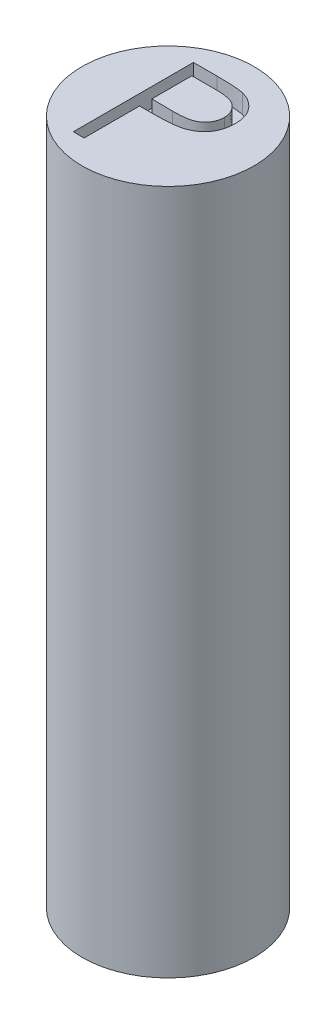
SolidWorks part; units mm, degrees
ref_plane "Front Plane" through (0, 0, 0) normal (0, 0, 1) x (1, 0, 0)
ref_plane "Top Plane" through (0, 0, 0) normal (0, 1, 0) x (1, 0, 0)
ref_plane "Right Plane" through (0, 0, 0) normal (1, 0, 0) x (0, 0, -1)
sketch "Sketch1" plane through (0, 0, 0) normal (0, 1, 0) x (1, 0, 0)
  circle A0 centre (0, 0) radius 9.1
  dimension "D1" = 18.2
extrude "Boss-Extrude1" add sketch "Sketch1" along normal blind 72.5
sketch "Sketch3" plane through (0, 72.5, 0) normal (0, 1, 0) x (1, 0, 0)
  line L1 (6.4347, -6.4347) -> (-6.4347, -6.4347) construction
  line L2 (6.4347, -6.4347) -> (6.4347, 6.4347) construction
  line L3 (6.4347, 6.4347) -> (-6.4347, 6.4347) construction
  line L4 (-6.4347, -6.4347) -> (-6.4347, 6.4347) construction
  line L5 (6.4347, -6.4347) -> (-6.4347, 6.4347) construction
  line L6 (6.4347, 6.4347) -> (-6.4347, -6.4347) construction
  circle A0 centre (0, 0) radius 9.1 construction
  text T0 "P" font "Century Gothic" height in points 48
  point P0 (0, 0)
extrude "Cut-Extrude2" cut sketch "Sketch3" against normal blind 2
equation "\"diameter\"= 18.20mm"
equation "\"unprot_height\"= 65.20mm"
equation "\"D1@Sketch1\"=\"diameter\""
equation "\"prot_height\"= 72.5mm"
equation "\"D1@Boss-Extrude1\"=\"prot_height\""
